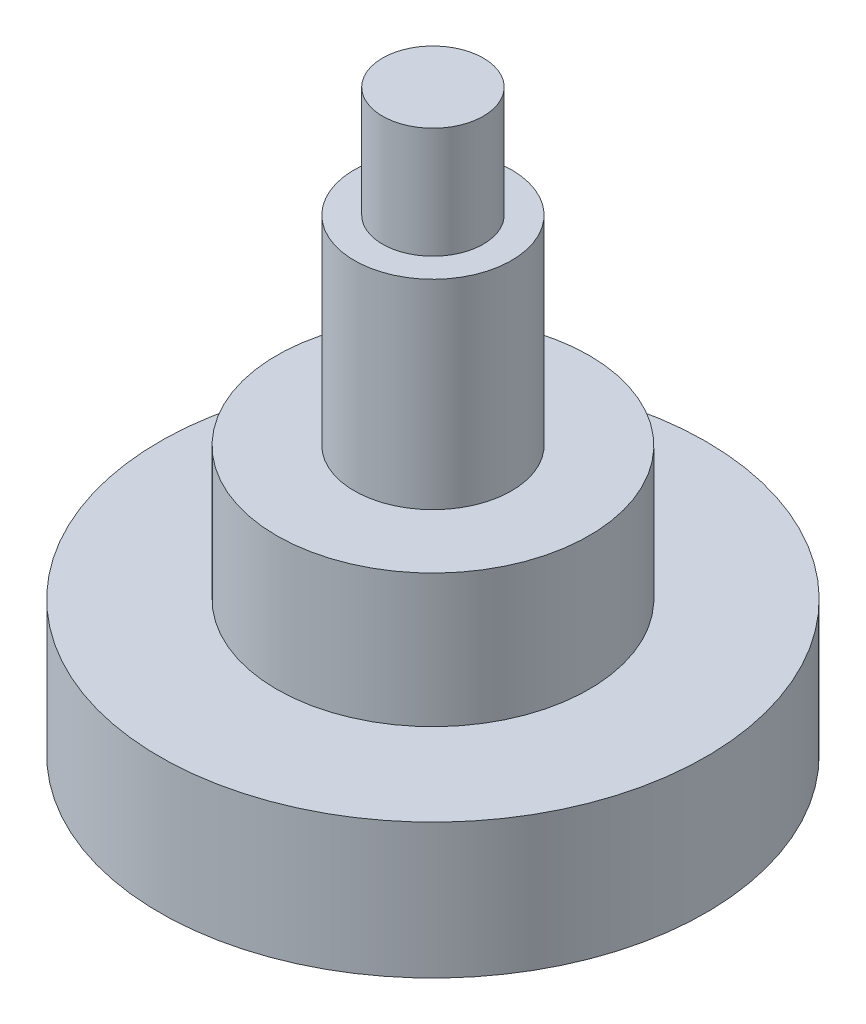
SolidWorks part; units mm, degrees
ref_plane "正面" through (0, 0, 0) normal (0, 0, 1) x (1, 0, 0)
ref_plane "平面" through (0, 0, 0) normal (0, 1, 0) x (1, 0, 0)
ref_plane "右側面" through (0, 0, 0) normal (1, 0, 0) x (0, 0, -1)
sketch "ｽｹｯﾁ1" plane through (0, 0, 0) normal (0, 0, 1) x (1, 0, 0)
  line L0 (0, 0) -> (0, 17.1)
  line L1 (0, 17.1) -> (1.25, 17.1)
  line L2 (1.25, 17.1) -> (1.25, 14.35)
  line L3 (1.25, 14.35) -> (1.95, 14.35)
  line L5 (3.875, 6.1) -> (6.775, 6.1)
  line L6 (6.775, 6.1) -> (6.775, 2.75)
  line L7 (6.775, 2.75) -> (1.25, 2.75)
  line L8 (1.25, 2.75) -> (1.25, 0)
  line L9 (1.25, 0) -> (0, 0)
  line L10 (1.95, 14.35) -> (1.95, 9.4)
  line L11 (1.95, 9.4) -> (3.875, 9.4)
  line L12 (3.875, 9.4) -> (3.875, 6.1)
  dimension "D1" = 3.35
  dimension "D2" = 1.25
  dimension "D3" = 2.75
  dimension "D4" = 2.75
  dimension "D5" = 4.95
  dimension "D6" = 3.3
  dimension "D7" = 1.95
  dimension "D8" = 3.875
  dimension "D9" = 6.775
  dimension "D10" = 17.1
revolve "回転1" add sketch "ｽｹｯﾁ1" angle 360 about L0
